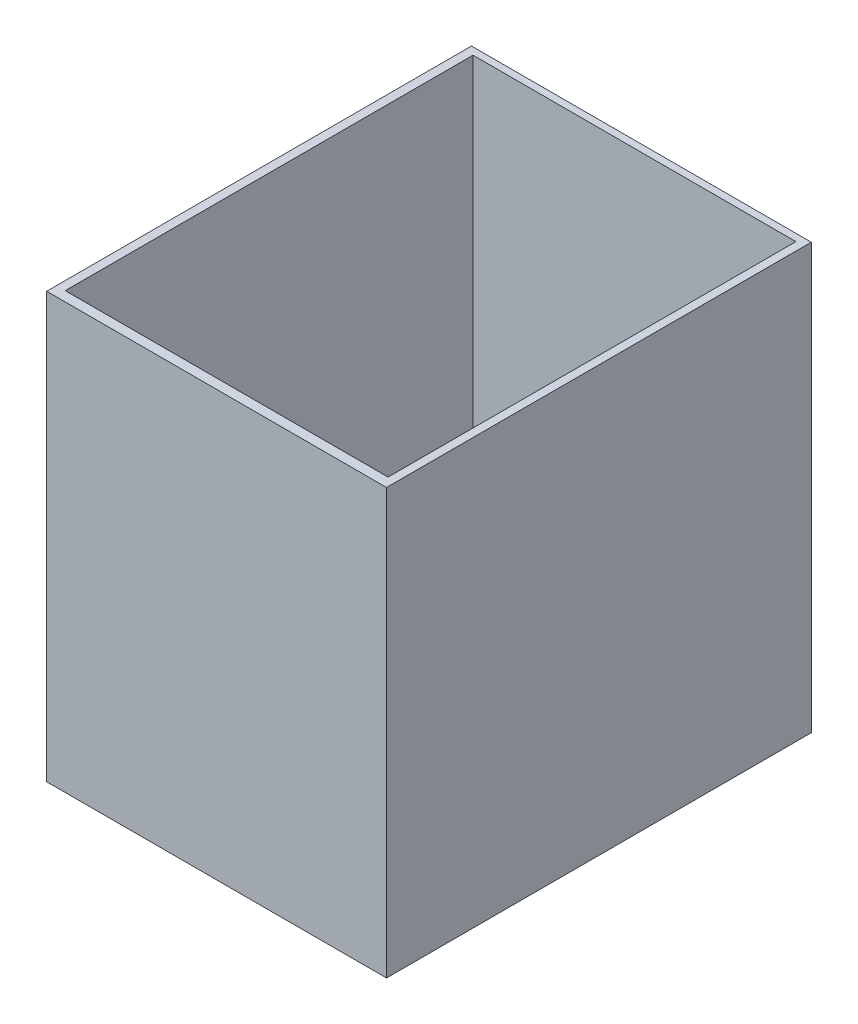
SolidWorks part; units mm, degrees
ref_plane "Front Plane" through (0, 0, 0) normal (0, 0, 1) x (1, 0, 0)
ref_plane "Top Plane" through (0, 0, 0) normal (0, 1, 0) x (1, 0, 0)
ref_plane "Right Plane" through (0, 0, 0) normal (1, 0, 0) x (0, 0, -1)
sketch "Sketch1" plane through (0, 0, 0) normal (0, 0, 1) x (1, 0, 0)
  line L1 (-400, -500) -> (400, -500)
  line L2 (-400, -500) -> (-400, 500)
  line L3 (-400, 500) -> (400, 500)
  line L4 (400, -500) -> (400, 500)
  line L5 (-400, -500) -> (400, 500) construction
  line L6 (-400, 500) -> (400, -500) construction
  point P0 (0, 0)
  dimension "D1" = 800
  dimension "D2" = 1000
extrude "Boss-Extrude1" add sketch "Sketch1" along normal blind 1000 contours L3 L4 L1 L2
sketch "Sketch5" plane through (0, 500, 0) normal (0, 1, 0) x (1, 0, 0)
  line L1 (-379.4116, -16.9068) -> (380.5884, -16.9068)
  line L2 (-379.4116, -16.9068) -> (-379.4116, -976.9068)
  line L3 (-379.4116, -976.9068) -> (380.5884, -976.9068)
  line L4 (380.5884, -16.9068) -> (380.5884, -976.9068)
  dimension "D1" = 960
  dimension "D2" = 760
extrude "Cut-Extrude1" cut sketch "Sketch5" against normal blind 960
